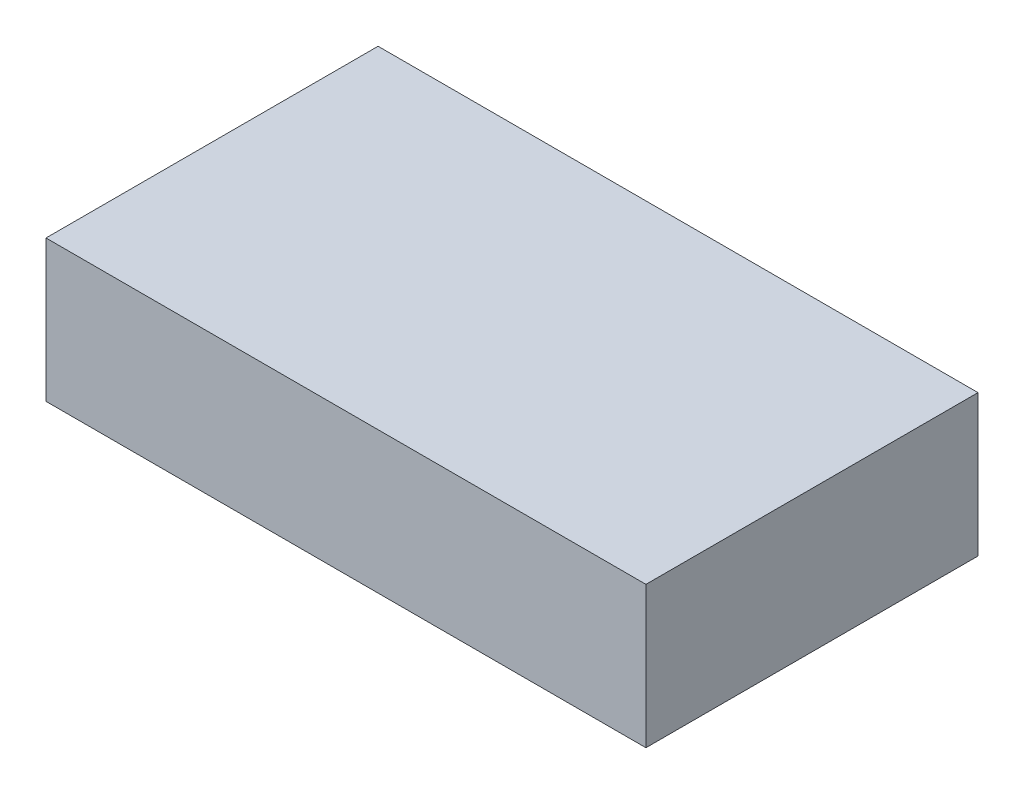
SolidWorks part; units mm, degrees
ref_plane "Спереди" through (0, 0, 0) normal (0, 0, 1) x (1, 0, 0)
ref_plane "Сверху" through (0, 0, 0) normal (0, 1, 0) x (1, 0, 0)
ref_plane "Справа" through (0, 0, 0) normal (1, 0, 0) x (0, 0, -1)
other "Configuration Table"
sketch "Эскиз1" plane through (0, 0, 0) normal (0, 1, 0) x (1, 0, 0)
  line L1 (-38.3, -21.2) -> (38.3, -21.2)
  line L2 (-38.3, -21.2) -> (-38.3, 21.2)
  line L3 (-38.3, 21.2) -> (38.3, 21.2)
  line L4 (38.3, -21.2) -> (38.3, 21.2)
  line L5 (-38.3, -21.2) -> (38.3, 21.2) construction
  line L6 (-38.3, 21.2) -> (38.3, -21.2) construction
  point P0 (0, 0)
  dimension "D1" = 76.6
  dimension "D2" = 42.4
extrude "Бобышка-Вытянуть1" add sketch "Эскиз1" along normal blind 18.07
